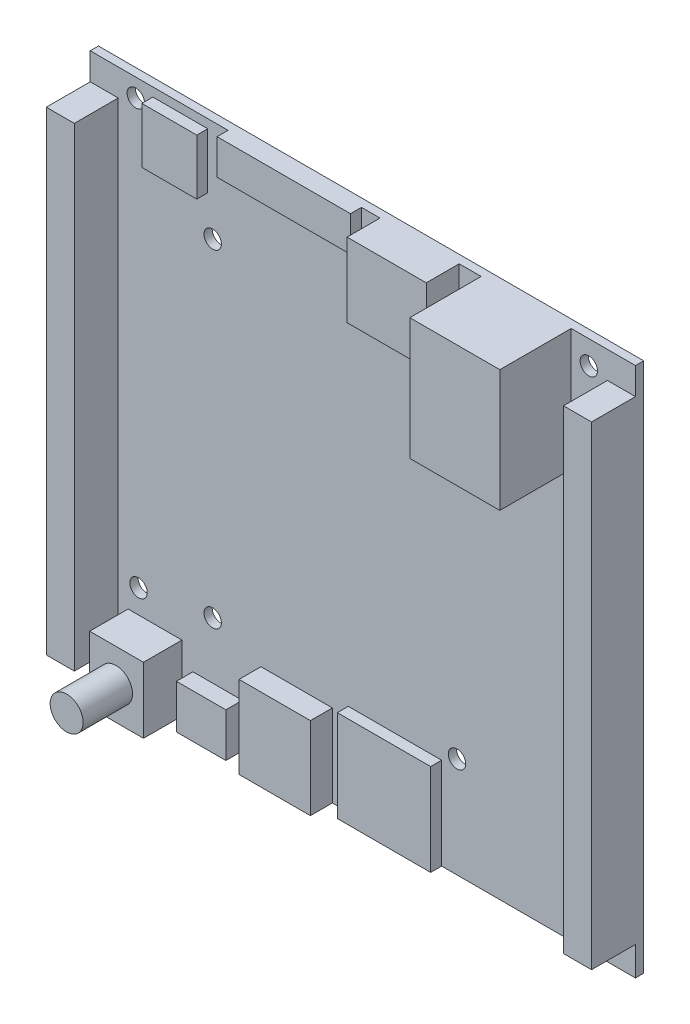
SolidWorks part; units mm, degrees
ref_plane "前视基准面" through (0, 0, 0) normal (0, 0, 1) x (1, 0, 0)
ref_plane "上视基准面" through (0, 0, 0) normal (0, 1, 0) x (1, 0, 0)
ref_plane "右视基准面" through (0, 0, 0) normal (1, 0, 0) x (0, 0, -1)
sketch "草图1" plane through (0, 0, 0) normal (0, 0, 1) x (1, 0, 0)
  line L0 (0, 4.42) -> (53.34, 4.42) construction
  line L1 (0, 0) -> (53.34, 0) construction
  line L2 (0, 0) -> (0, 68.58) construction
  line L3 (0, 68.58) -> (53.34, 68.58) construction
  line L4 (53.34, 0) -> (53.34, 68.58) construction
  line L5 (0, 64.16) -> (53.34, 64.16) construction
  line L6 (4.42, 68.58) -> (4.42, 0) construction
  line L7 (48.92, 68.58) -> (48.92, 0) construction
  line L9 (-17.88, 82.72) -> (81.42, 82.72)
  line L10 (-17.88, 82.72) -> (-17.88, -13.88)
  line L11 (-17.88, -13.88) -> (81.42, -13.88)
  line L12 (81.42, 82.72) -> (81.42, -13.88)
  circle A0 centre (48.92, 64.16) radius 1.585
  circle A1 centre (4.42, 64.16) radius 1.585
  circle A2 centre (4.42, 4.42) radius 1.585
  circle A3 centre (48.92, 4.42) radius 1.585
  circle A4 centre (-9.08, 2.42) radius 1.585
  circle A5 centre (72.92, -9.58) radius 1.585
  circle A6 centre (72.92, 78.42) radius 1.585
  circle A7 centre (-9.58, 79.42) radius 1.585
  dimension "D7" = 3.17
  dimension "D8" = 3.17
  dimension "D9" = 3.17
  dimension "D10" = 3.17
  dimension "D15" = 3.17
  dimension "D18" = 3.17
  dimension "D21" = 3.17
  dimension "D24" = 3.17
  dimension "D1" = 68.58
  dimension "D2" = 53.34
  dimension "D3" = 4.42
  dimension "D4" = 4.42
  dimension "D5" = 4.42
  dimension "D6" = 4.42
  dimension "D11" = 99.3
  dimension "D12" = 96.6
  dimension "D13" = 13.5
  dimension "D14" = 2
  dimension "D16" = 68.5
  dimension "D17" = 14
  dimension "D19" = 74
  dimension "D20" = 68.5
  dimension "D22" = 75
  dimension "D23" = 14
  dimension "D25" = 22.3
  dimension "D26" = 18.3
extrude "凸台-拉伸1" add sketch "草图1" along normal blind 1.5
sketch "草图2" plane through (0, 0, 1.5) normal (0, 0, 1) x (1, 0, 0)
  line L0 (-17.88, -13.88) -> (81.42, -13.88) construction
  line L1 (-10.98, -13.88) -> (-1.18, -13.88)
  line L2 (-10.98, -13.88) -> (-10.98, -1.88)
  line L3 (-10.98, -1.88) -> (-1.18, -1.88)
  line L4 (-1.18, -13.88) -> (-1.18, -1.88)
  circle A0 centre (4.42, 4.42) radius 1.585 construction
  dimension "D1" = 6.3
  dimension "D2" = 5.6
  dimension "D3" = 9.8
extrude "凸台-拉伸2" add sketch "草图2" along normal blind 7
sketch "草图3" plane through (0, 0, 8.5) normal (0, 0, 1) x (1, 0, 0)
  line L0 (-1.18, -13.88) -> (-1.18, -1.88) construction
  line L1 (-10.98, -13.88) -> (-1.18, -13.88) construction
  circle A0 centre (-6.18, -7.88) radius 3
  point P6 (-6.2377, -8.4095)
  dimension "D3" = 6
  dimension "D1" = 5
  dimension "D2" = 6
extrude "凸台-拉伸3" add sketch "草图3" along normal blind 9
sketch "草图4" plane through (0, 0, 1.5) normal (0, 0, 1) x (1, 0, 0)
  line L0 (81.42, -13.88) -> (81.42, 82.72) construction
  line L1 (81.42, 77.82) -> (76.32, 77.82)
  line L2 (81.42, 77.82) -> (81.42, -8.58)
  line L3 (81.42, -8.58) -> (76.32, -8.58)
  line L4 (76.32, 77.82) -> (76.32, -8.58)
  line L5 (-17.88, 82.72) -> (-17.88, -13.88) construction
  line L6 (-17.88, 77.82) -> (-12.78, 77.82)
  line L7 (-17.88, 77.82) -> (-17.88, -8.58)
  line L8 (-17.88, -8.58) -> (-12.78, -8.58)
  line L9 (-12.78, 77.82) -> (-12.78, -8.58)
  line L10 (-1.18, -13.88) -> (81.42, -13.88) construction
  line L11 (81.42, 82.72) -> (-17.88, 82.72) construction
  line L12 (-17.88, -13.88) -> (-10.98, -13.88) construction
  dimension "D1" = 5.3
  dimension "D2" = 5.1
  dimension "D3" = 4.9
  dimension "D4" = 4.9
  dimension "D5" = 5.1
  dimension "D6" = 5.3
extrude "凸台-拉伸4" add sketch "草图4" along normal blind 8
sketch "草图5" plane through (0, 0, 1.5) normal (0, 0, 1) x (1, 0, 0)
  line L0 (81.42, 82.72) -> (-17.88, 82.72) construction
  line L1 (69.72, 82.72) -> (53.32, 82.72)
  line L2 (69.72, 82.72) -> (69.72, 60.52)
  line L3 (69.72, 60.52) -> (53.32, 60.52)
  line L4 (53.32, 82.72) -> (53.32, 60.52)
  line L5 (81.42, 77.82) -> (81.42, 82.72) construction
  dimension "D1" = 11.7
  dimension "D2" = 22.2
  dimension "D3" = 16.4
extrude "凸台-拉伸5" add sketch "草图5" along normal blind 13
sketch "草图6" plane through (0, 0, 1.5) normal (0, 0, 1) x (1, 0, 0)
  line L0 (53.32, 82.72) -> (-17.88, 82.72) construction
  line L1 (49.32, 82.72) -> (34.9, 82.72)
  line L2 (49.32, 82.72) -> (49.32, 69.22)
  line L3 (49.32, 69.22) -> (34.9, 69.22)
  line L4 (34.9, 82.72) -> (34.9, 69.22)
  line L5 (81.42, 77.82) -> (81.42, 82.72) construction
  dimension "D1" = 32.1
  dimension "D2" = 13.5
  dimension "D3" = 14.42
extrude "凸台-拉伸6" add sketch "草图6" along normal blind 6
sketch "草图7" plane through (0, 0, 1.5) normal (0, 0, 1) x (1, 0, 0)
  line L0 (34.9, 82.72) -> (-17.88, 82.72) construction
  line L1 (31.52, 82.72) -> (7.22, 82.72)
  line L2 (31.52, 82.72) -> (31.52, 76.32)
  line L3 (31.52, 76.32) -> (7.22, 76.32)
  line L4 (7.22, 82.72) -> (7.22, 76.32)
  line L5 (-17.88, 82.72) -> (-17.88, 77.82) construction
  dimension "D1" = 25.1
  dimension "D2" = 6.4
  dimension "D3" = 24.3
extrude "凸台-拉伸7" add sketch "草图7" along normal blind 2
sketch "草图8" plane through (0, 0, 1.5) normal (0, 0, 1) x (1, 0, 0)
  line L0 (-17.88, 77.82) -> (-17.88, -8.58) construction
  line L1 (-6.48, 81.12) -> (3.52, 81.12)
  line L2 (-6.48, 81.12) -> (-6.48, 71.02)
  line L3 (-6.48, 71.02) -> (3.52, 71.02)
  line L4 (3.52, 81.12) -> (3.52, 71.02)
  line L5 (7.22, 82.72) -> (-17.88, 82.72) construction
  dimension "D1" = 11.4
  dimension "D2" = 1.6
  dimension "D3" = 10
  dimension "D4" = 10.1
extrude "凸台-拉伸8" add sketch "草图8" along normal blind 2
sketch "草图9" plane through (0, 0, 1.5) normal (0, 0, 1) x (1, 0, 0)
  line L0 (-1.18, -13.88) -> (81.42, -13.88) construction
  line L1 (0.82, -13.88) -> (9.82, -13.88)
  line L2 (0.82, -13.88) -> (0.82, -5.88)
  line L3 (0.82, -5.88) -> (9.82, -5.88)
  line L4 (9.82, -13.88) -> (9.82, -5.88)
  line L5 (-17.88, -8.58) -> (-17.88, -13.88) construction
  dimension "D1" = 18.7
  dimension "D2" = 8
  dimension "D3" = 9
extrude "凸台-拉伸9" add sketch "草图9" along normal blind 3
sketch "草图10" plane through (0, 0, 1.5) normal (0, 0, 1) x (1, 0, 0)
  line L0 (9.82, -13.88) -> (81.42, -13.88) construction
  line L1 (13.22, -13.88) -> (26.22, -13.88)
  line L2 (13.22, -13.88) -> (13.22, 1.12)
  line L3 (13.22, 1.12) -> (26.22, 1.12)
  line L4 (26.22, -13.88) -> (26.22, 1.12)
  line L5 (-17.88, -8.58) -> (-17.88, -13.88) construction
  dimension "D1" = 31.1
  dimension "D2" = 15
  dimension "D3" = 13
extrude "凸台-拉伸10" add sketch "草图10" along normal blind 4
sketch "草图11" plane through (0, 0, 1.5) normal (0, 0, 1) x (1, 0, 0)
  line L0 (26.22, -13.88) -> (81.42, -13.88) construction
  line L1 (29.12, -13.88) -> (46.12, -13.88)
  line L2 (29.12, -13.88) -> (29.12, 2.82)
  line L3 (29.12, 2.82) -> (46.12, 2.82)
  line L4 (46.12, -13.88) -> (46.12, 2.82)
  line L5 (-17.88, -8.58) -> (-17.88, -13.88) construction
  dimension "D1" = 47
  dimension "D2" = 16.7
  dimension "D3" = 17
extrude "凸台-拉伸11" add sketch "草图11" along normal blind 2
